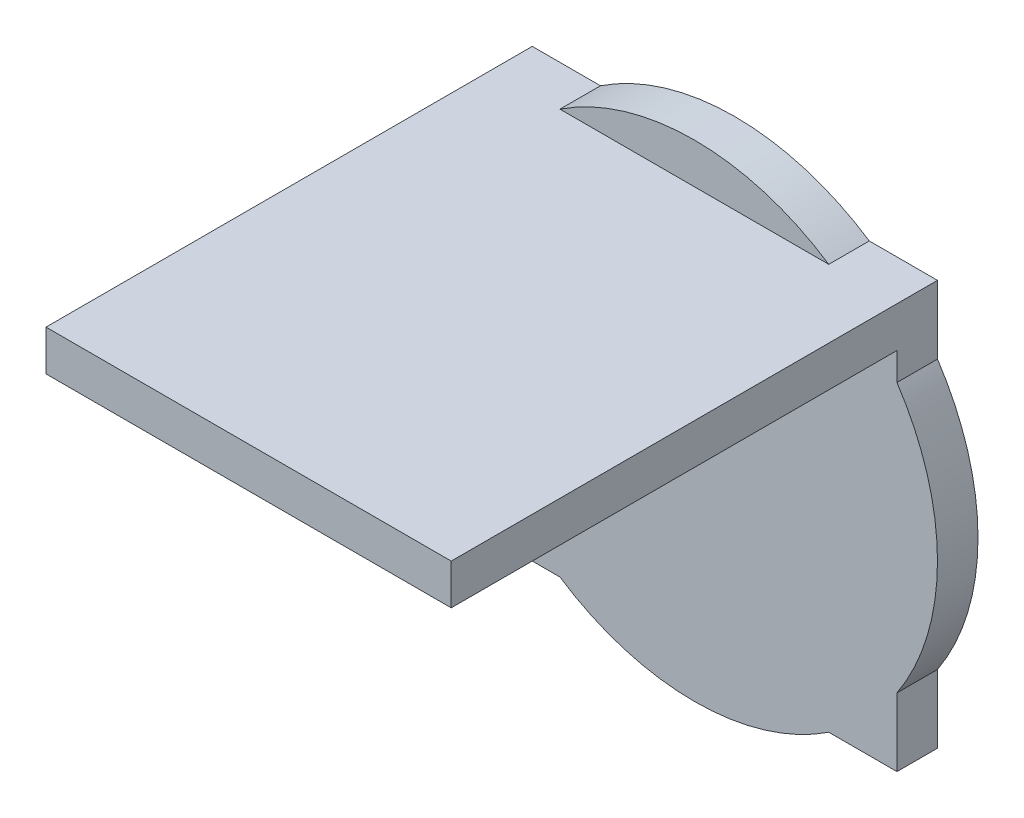
SolidWorks part; units mm, degrees
ref_plane "前视基准面" through (0, 0, 0) normal (0, 0, 1) x (1, 0, 0)
ref_plane "上视基准面" through (0, 0, 0) normal (0, 1, 0) x (1, 0, 0)
ref_plane "右视基准面" through (0, 0, 0) normal (1, 0, 0) x (0, 0, -1)
other "Configuration Table"
sketch "草图1" plane through (0, 0, 0) normal (0, 0, 1) x (1, 0, 0)
  circle A0 centre (0, 0) radius 300
extrude "凸台-拉伸1" add sketch "草图1" along normal blind 50
sketch "草图2" plane through (0, 0, 0) normal (0, 0, 1) x (1, 0, 0)
  line L1 (-250, -250) -> (250, -250)
  line L2 (-250, -250) -> (-250, 250)
  line L3 (-250, 250) -> (250, 250)
  line L4 (250, -250) -> (250, 250)
  line L5 (-250, -250) -> (250, 250) construction
  line L6 (-250, 250) -> (250, -250) construction
  point P0 (0, 0)
extrude "凸台-拉伸2" add sketch "草图2" along normal blind 50
sketch "草图3" plane through (0, 0, 0) normal (0, 0, 1) x (1, 0, 0)
  line L1 (-250, 200) -> (250, 200)
  line L2 (-250, 200) -> (-250, 250)
  line L3 (-250, 250) -> (250, 250)
  line L4 (250, 200) -> (250, 250)
  line L5 (-250, 200) -> (250, 250) construction
  line L6 (-250, 250) -> (250, 200) construction
  point P0 (0, 225)
extrude "凸台-拉伸3" add sketch "草图3" along normal blind 600
